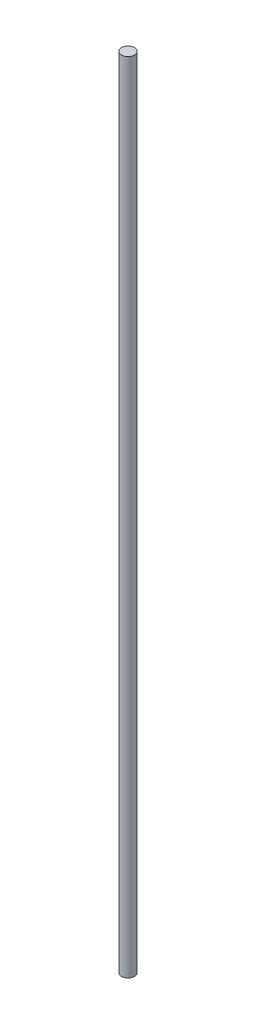
SolidWorks part; units mm, degrees
ref_plane "Front Plane" through (0, 0, 0) normal (0, 0, 1) x (1, 0, 0)
ref_plane "Top Plane" through (0, 0, 0) normal (0, 1, 0) x (1, 0, 0)
ref_plane "Right Plane" through (0, 0, 0) normal (1, 0, 0) x (0, 0, -1)
sketch "Sketch1" plane through (0, 0, 0) normal (0, 1, 0) x (1, 0, 0)
  circle A0 centre (0, 0) radius 4
extrude "Boss-Extrude1" add sketch "Sketch1" along normal blind 490
